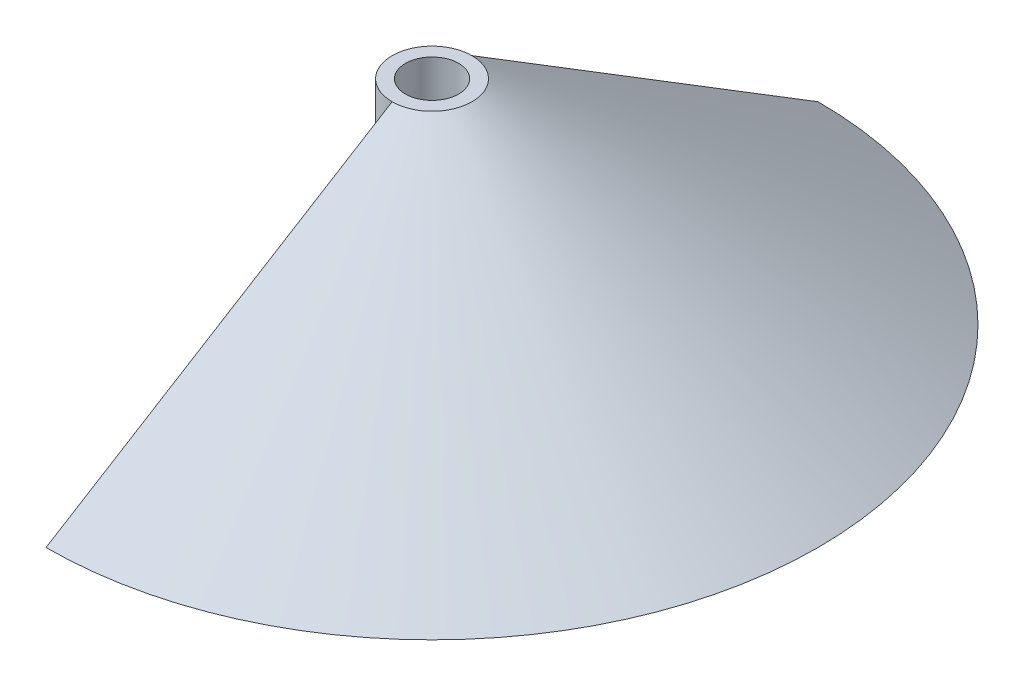
SolidWorks part; units mm, degrees
ref_plane "Alzado" through (0, 0, 0) normal (0, 0, 1) x (1, 0, 0)
ref_plane "Planta" through (0, 0, 0) normal (0, 1, 0) x (1, 0, 0)
ref_plane "Vista lateral" through (0, 0, 0) normal (1, 0, 0) x (0, 0, -1)
sketch "Croquis2" plane through (0, 0, 0) normal (1, 0, 0) x (0, 0, -1)
  line L0 (0, -8) -> (0, 8)
  line L1 (0, 8) -> (3, 8)
  line L2 (3, 8) -> (29, -8)
  line L3 (29, -8) -> (0, -8)
  line L4 (3, 8) -> (3, -8) construction
  point P4 (0, 0)
  dimension "D1" = 3
  dimension "D2" = 26
  dimension "D3" = 16
revolve "Revolución1" add sketch "Croquis2" angle 360 about L0
sketch "Croquis3" plane through (0, 8, 0) normal (0, 1, 0) x (1, 0, 0)
  line L0 (0, 3) -> (0, 40.3254)
  line L1 (0, -3) -> (0, -39.9637)
  line L2 (0, 40.3254) -> (-47.5507, 40.3254)
  line L3 (-47.5507, 40.3254) -> (-47.5507, -39.9637)
  line L4 (-47.5507, -39.9637) -> (0, -39.9637)
  circle A0 centre (0, 0) radius 3 construction
  arc A1 (0, 3) -> (0, -3) centre (0, 0) ccw
extrude "Cortar-Extruir1" cut sketch "Croquis3" against normal through all
sketch "Croquis4" plane through (0, 8, 0) normal (0, 1, 0) x (1, 0, 0)
  circle A0 centre (0, 0) radius 2
  dimension "D1" = 4
extrude "Cortar-Extruir2" cut sketch "Croquis4" against normal through all
